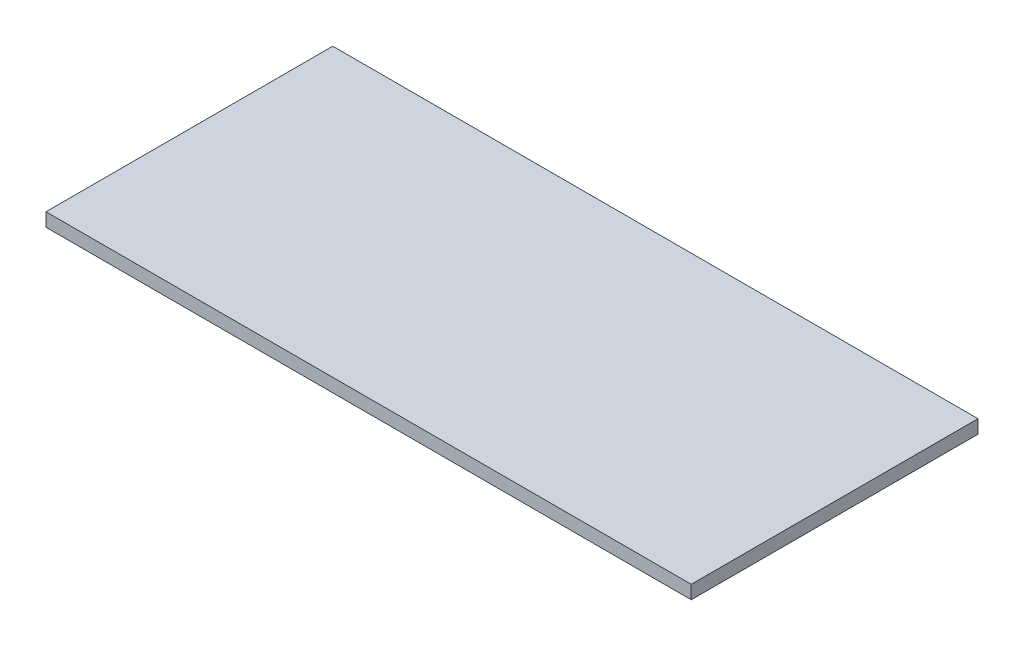
SolidWorks part; units mm, degrees
ref_plane "Front Plane" through (0, 0, 0) normal (0, 0, 1) x (1, 0, 0)
ref_plane "Top Plane" through (0, 0, 0) normal (0, 1, 0) x (1, 0, 0)
ref_plane "Right Plane" through (0, 0, 0) normal (1, 0, 0) x (0, 0, -1)
sketch "Sketch1" plane through (0, 0, 0) normal (0, 1, 0) x (1, 0, 0)
  line L1 (0, 0) -> (914.4, 0)
  line L2 (0, 0) -> (0, 406.4)
  line L3 (0, 406.4) -> (914.4, 406.4)
  line L4 (914.4, 0) -> (914.4, 406.4)
  dimension "D1" = 914.4
  dimension "D2" = 406.4
extrude "Boss-Extrude1" add sketch "Sketch1" along normal blind 19.05
